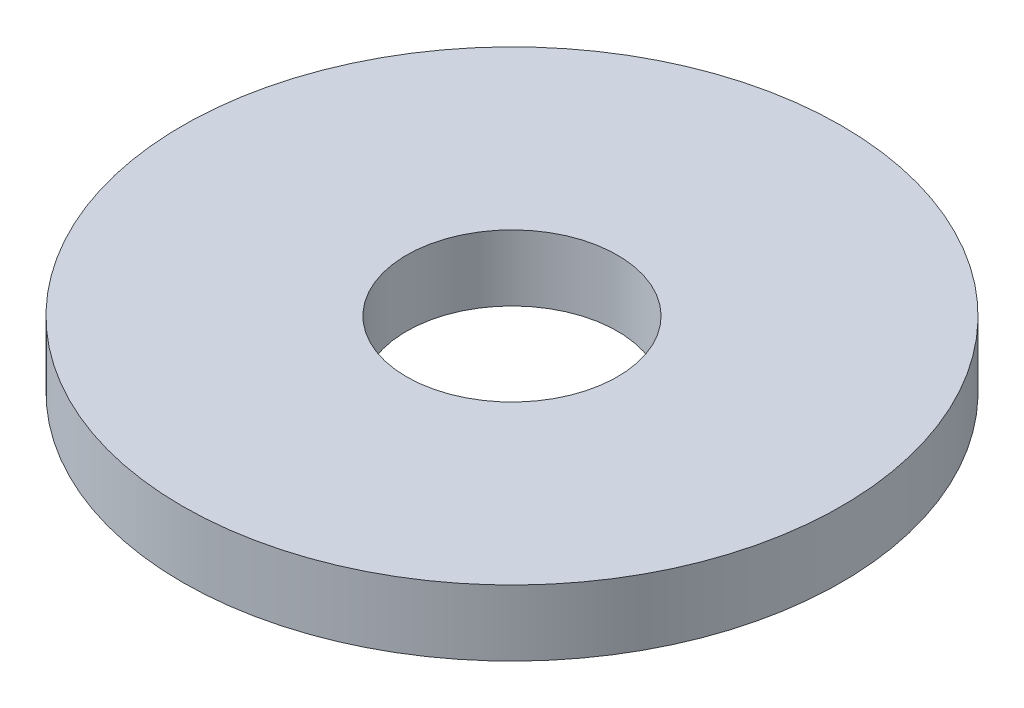
SolidWorks part; units mm, degrees
ref_plane "Front Plane" through (0, 0, 0) normal (0, 0, 1) x (1, 0, 0)
ref_plane "Top Plane" through (0, 0, 0) normal (0, 1, 0) x (1, 0, 0)
ref_plane "Right Plane" through (0, 0, 0) normal (1, 0, 0) x (0, 0, -1)
sketch "Sketch1" plane through (0, 0, 0) normal (0, 1, 0) x (1, 0, 0)
  circle A0 centre (0, 0) radius 1.6
  circle A1 centre (0, 0) radius 5
  dimension "D1" = 3.2
  dimension "D2" = 10
extrude "Boss-Extrude1" add sketch "Sketch1" along normal blind 1
